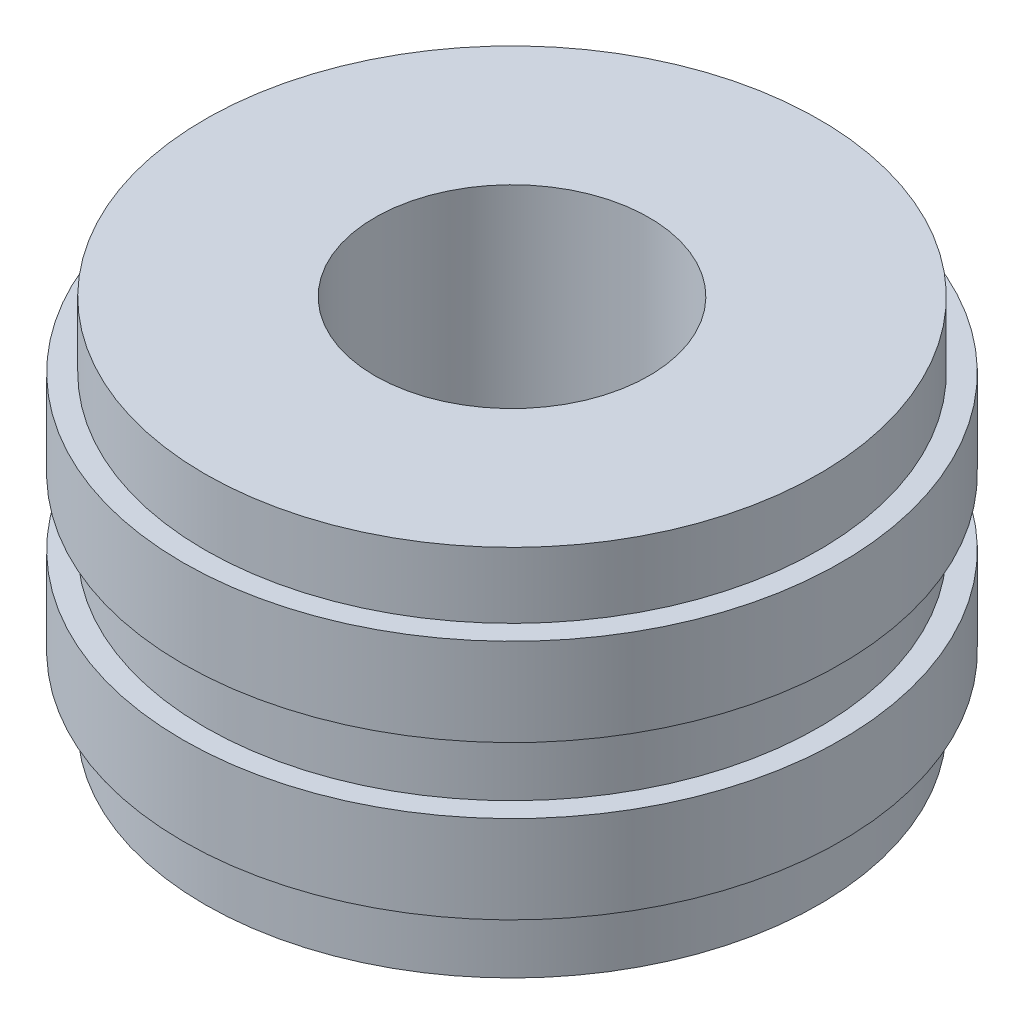
SolidWorks part; units mm, degrees
ref_plane "前视基准面" through (0, 0, 0) normal (0, 0, 1) x (1, 0, 0)
ref_plane "上视基准面" through (0, 0, 0) normal (0, 1, 0) x (1, 0, 0)
ref_plane "右视基准面" through (0, 0, 0) normal (1, 0, 0) x (0, 0, -1)
sketch "草图1" plane through (0, 0, 0) normal (0, 1, 0) x (1, 0, 0)
  circle A0 centre (0, 0) radius 12.5
  circle A1 centre (0, 0) radius 30
  dimension "D1" = 60
  dimension "D2" = 25
extrude "凸台-拉伸1" add sketch "草图1" along normal blind 34
sketch "草图2" plane through (0, 34, 0) normal (0, 1, 0) x (1, 0, 0)
  circle A0 centre (0, 0) radius 30
  circle A1 centre (0, 0) radius 28
  dimension "D1" = 56
extrude "切除-拉伸1" cut sketch "草图2" against normal blind 6
pattern_linear "阵列(线性)1" count 3 spacing 14 along (0, -1, 0) of "切除-拉伸1"
